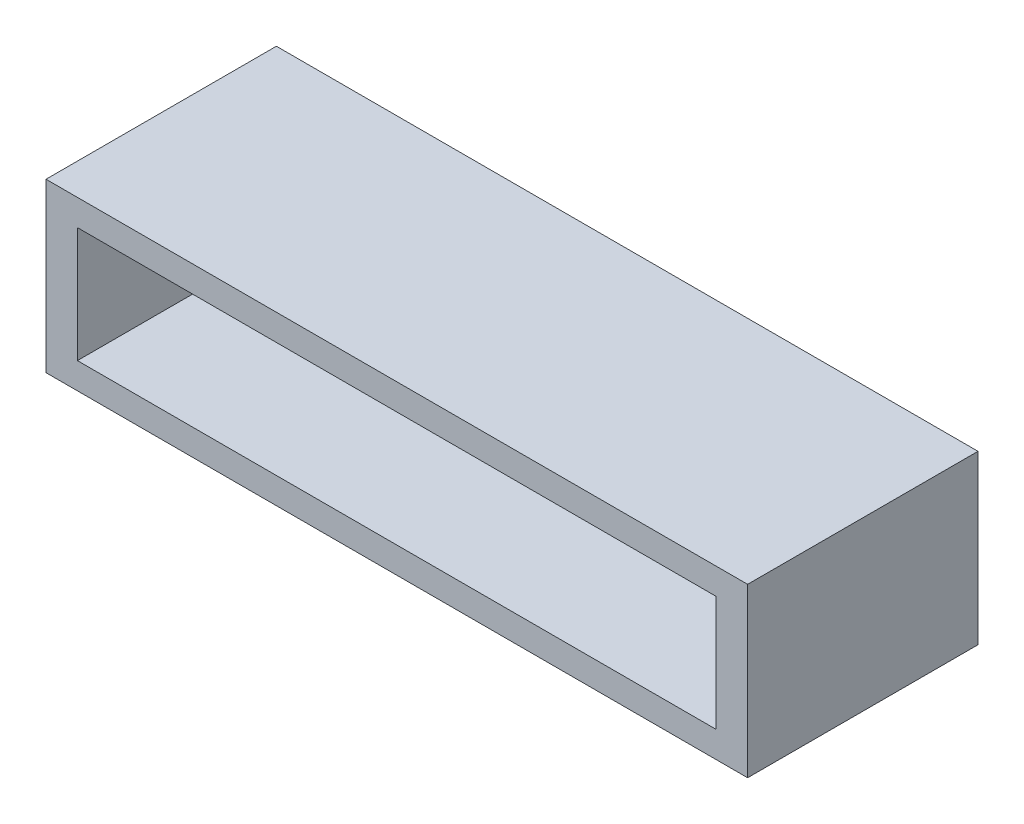
SolidWorks part; units mm, degrees
ref_plane "前视基准面" through (0, 0, 0) normal (0, 0, 1) x (1, 0, 0)
ref_plane "上视基准面" through (0, 0, 0) normal (0, 1, 0) x (1, 0, 0)
ref_plane "右视基准面" through (0, 0, 0) normal (1, 0, 0) x (0, 0, -1)
other "Configuration Table"
sketch "草图1" plane through (0, 0, 0) normal (0, 0, 1) x (1, 0, 0)
  line L1 (-30.5, -5.5) -> (30.5, -5.5)
  line L2 (-30.5, -5.5) -> (-30.5, 5.5)
  line L3 (-30.5, 5.5) -> (30.5, 5.5)
  line L4 (30.5, -5.5) -> (30.5, 5.5)
  line L5 (-30.5, -5.5) -> (30.5, 5.5) construction
  line L6 (-30.5, 5.5) -> (30.5, -5.5) construction
  line L7 (33.5, -8) -> (-33.5, -8)
  line L8 (33.5, -8) -> (33.5, 8)
  line L9 (33.5, 8) -> (-33.5, 8)
  line L10 (-33.5, -8) -> (-33.5, 8)
  line L11 (33.5, -8) -> (-33.5, 8) construction
  line L12 (33.5, 8) -> (-33.5, -8) construction
  point P0 (0, 0)
  point P6 (0, 0)
  dimension "D1" = 2.5
  dimension "D2" = 3
  dimension "D3" = 11
  dimension "D4" = 61
extrude "凸台-拉伸1" add sketch "草图1" along normal blind 22
